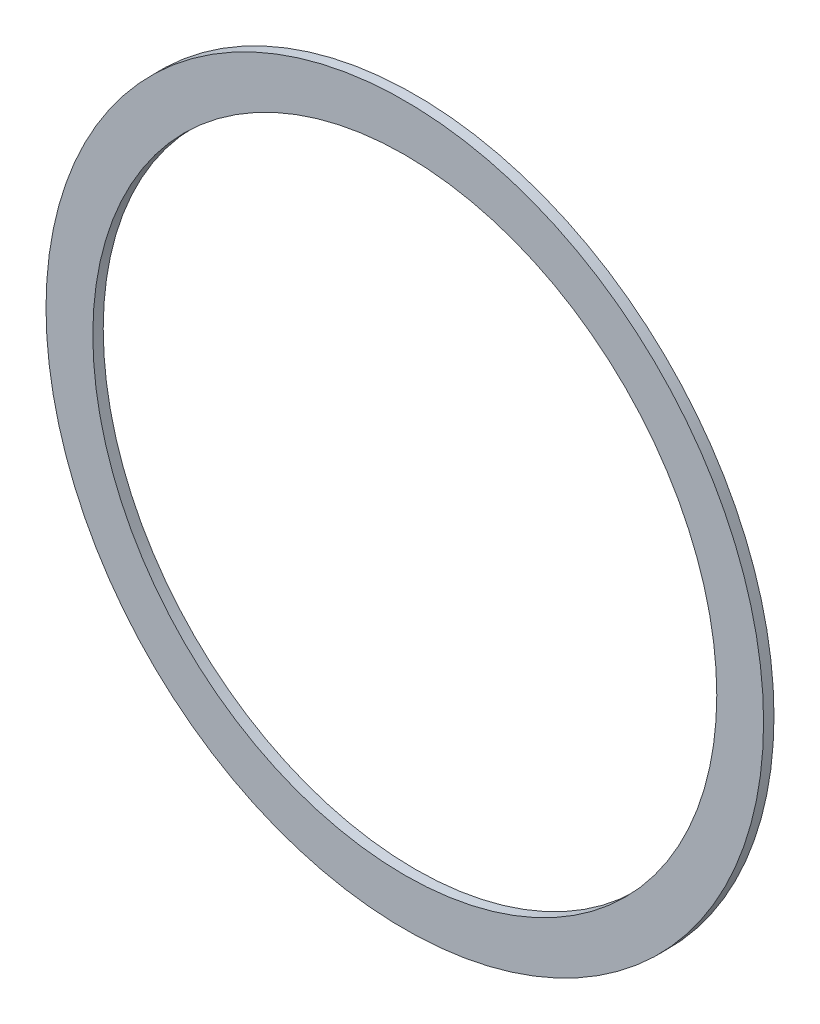
SolidWorks part; units mm, degrees
ref_plane "Front Plane" through (0, 0, 0) normal (0, 0, 1) x (1, 0, 0)
ref_plane "Top Plane" through (0, 0, 0) normal (0, 1, 0) x (1, 0, 0)
ref_plane "Right Plane" through (0, 0, 0) normal (1, 0, 0) x (0, 0, -1)
sketch "Sketch1" plane through (0, 0, 0) normal (0, 0, 1) x (1, 0, 0)
  circle A0 centre (0, 0) radius 60
  circle A1 centre (0, 0) radius 69
extrude "Boss-Extrude1" add sketch "Sketch1" along normal mid plane 2
